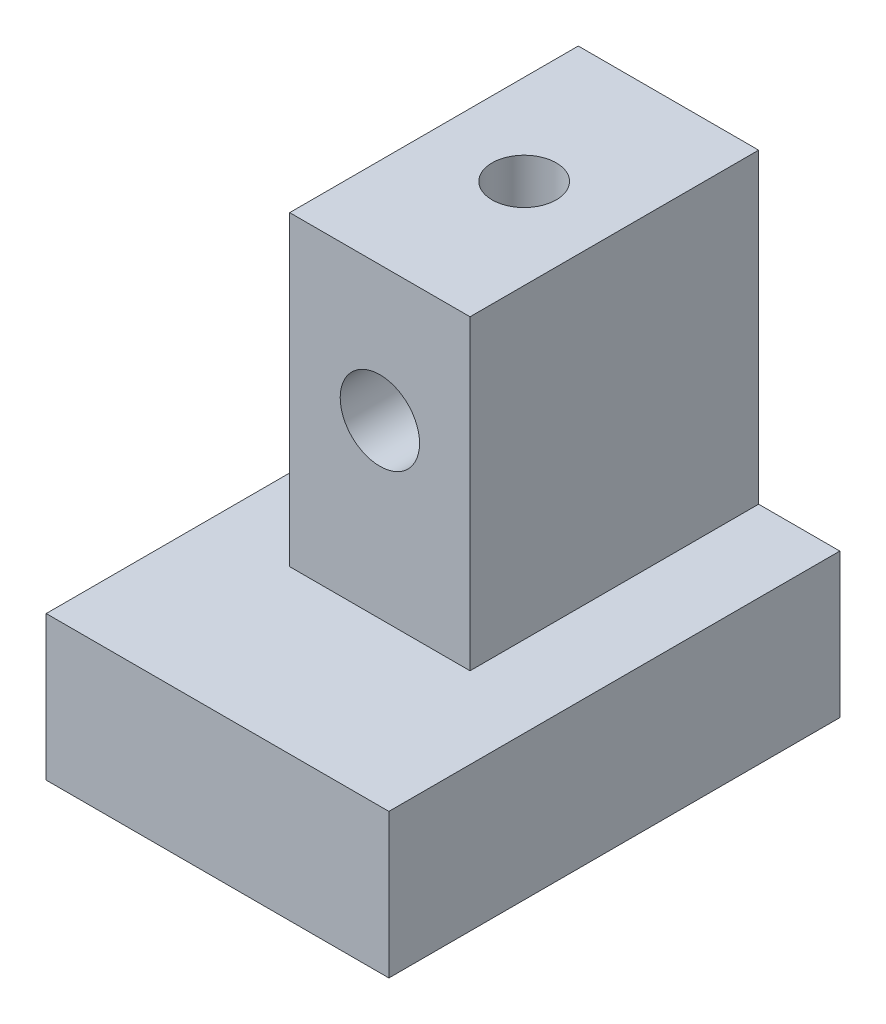
SolidWorks part; units mm, degrees
material "ABS PC"
ref_plane "Front Plane" through (0, 0, 0) normal (0, 0, 1) x (1, 0, 0)
ref_plane "Top Plane" through (0, 0, 0) normal (0, 1, 0) x (1, 0, 0)
ref_plane "Right Plane" through (0, 0, 0) normal (1, 0, 0) x (0, 0, -1)
sketch "Sketch1" plane through (0, 0, 0) normal (0, 0, 1) x (1, 0, 0)
  line L1 (-6.0325, -7.9375) -> (6.0325, -7.9375)
  line L2 (-6.0325, -7.9375) -> (-6.0325, 7.9375)
  line L3 (-6.0325, 7.9375) -> (6.0325, 7.9375)
  line L4 (6.0325, -7.9375) -> (6.0325, 7.9375)
  line L5 (-6.0325, -7.9375) -> (6.0325, 7.9375) construction
  line L6 (-6.0325, 7.9375) -> (6.0325, -7.9375) construction
  point P0 (0, 0)
  dimension "D1" = 12.065
  dimension "D2" = 15.875
extrude "Base" add sketch "Sketch1" along normal blind 15.875
sketch "Sketch3" plane through (0, 0, 0) normal (0, 0, -1) x (-1, 0, 0)
  line L0 (6.0325, -7.9375) -> (-6.0325, -7.9375) construction
  circle A0 centre (0, 3.1877) radius 1.397
  dimension "D1" = 2.794
  dimension "D2" = 11.1252
extrude "ShaftHole" cut sketch "Sketch3" against normal through all
sketch "Sketch7" plane through (0, 7.9375, 0) normal (0, 1, 0) x (1, 0, 0)
  line L1 (-3.175, -10.16) -> (3.175, -10.16)
  line L2 (-3.175, -10.16) -> (-3.175, 0)
  line L3 (-3.175, 0) -> (3.175, 0)
  line L4 (3.175, -10.16) -> (3.175, 0)
  line L5 (-8.4027, 3.7179) -> (9.7417, 3.7179)
  line L6 (-8.4027, 3.7179) -> (-8.4027, -18.9497)
  line L7 (-8.4027, -18.9497) -> (9.7417, -18.9497)
  line L8 (9.7417, 3.7179) -> (9.7417, -18.9497)
  line L15 (6.0325, 0) -> (-6.0325, 0) construction
  dimension "D1" = 6.35
  dimension "D2" = 10.16
extrude "Cut-Extrude1" cut sketch "Sketch7" against normal blind 10.795
hole_wizard "#4-40 Tapped Hole1" positions "Sketch5" profile "Sketch4" tap size "#4-40" standard "ANSI Inch"
sketch "Sketch5" plane through (5.1032, 7.9375, -0.9797) normal (0, -1, 0) x (0, 0, 1)
  line L1 (0.9797, 6.5002) -> (0.9797, 3.7062) construction
  line L2 (0.9797, 6.5002) -> (0.9797, 3.7062) construction
  line L3 (0.9797, 5.1032) -> (11.1397, 5.1032) construction
  line L14 (11.1397, 8.2782) -> (11.1397, 1.9282) construction
  point P0 (6.0597, 5.1032)
sketch "Sketch4" plane through (0, 7.9375, 5.08) normal (1, 0, 0) x (0, 0, 1)
  line L0 (0, 0) -> (0, 3.3528)
  line L1 (0, 3.3528) -> (1.1303, 3.3528)
  line L2 (1.1303, 3.3528) -> (1.1303, 0)
  line L5 (1.1303, 0) -> (0, 0)
  line L11 (0, -6.35) -> (0, 107.95) construction
  dimension "Thru Tap Drill Dia." = 2.2606
  dimension "Thru Tap Drill Depth" = 3.3528
cosmetic thread "Hole Thread1" parameters "D2"=2.8448
